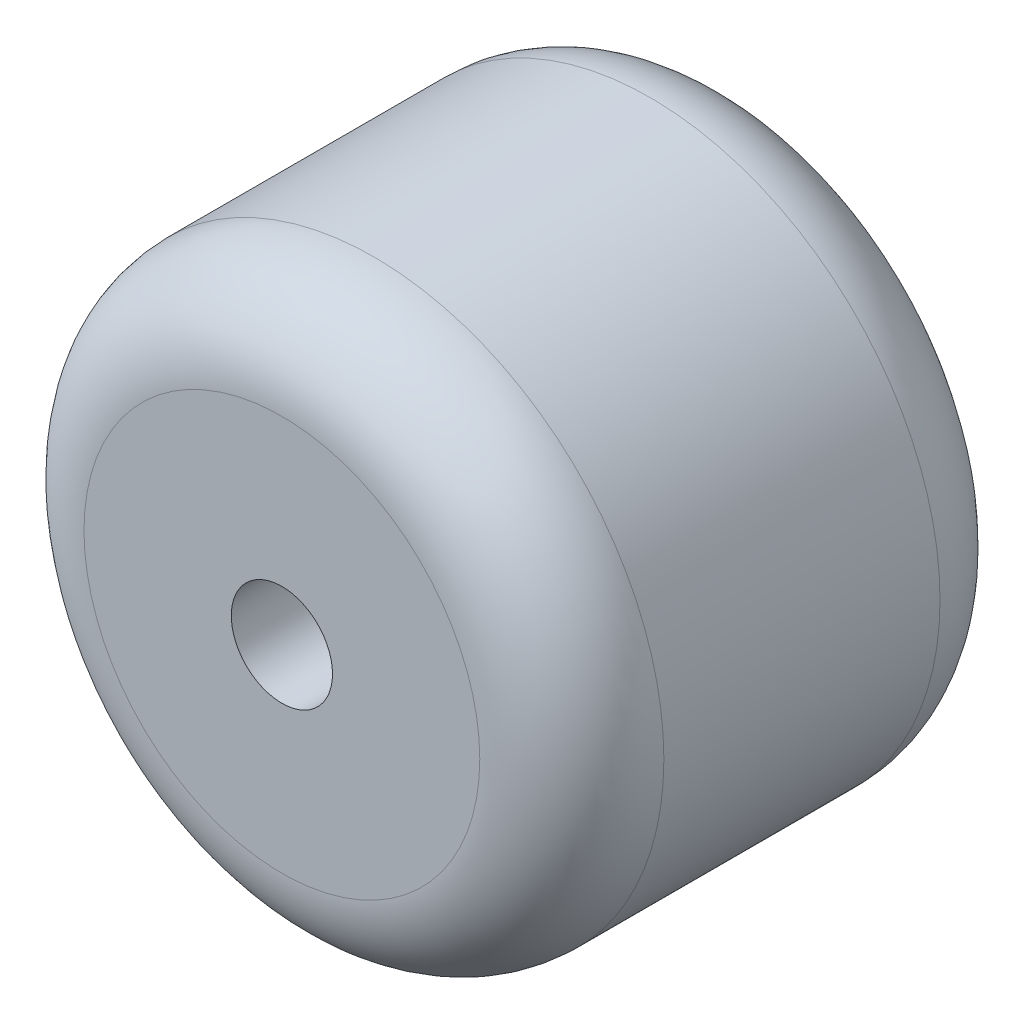
SolidWorks part; units mm, degrees
ref_plane "前视基准面" through (0, 0, 0) normal (0, 0, 1) x (1, 0, 0)
ref_plane "上视基准面" through (0, 0, 0) normal (0, 1, 0) x (1, 0, 0)
ref_plane "右视基准面" through (0, 0, 0) normal (1, 0, 0) x (0, 0, -1)
other "Configuration Table"
sketch "草图1" plane through (0, 0, 0) normal (0, 0, 1) x (1, 0, 0)
  circle A0 centre (0, 0) radius 2.75
  circle A1 centre (0, 0) radius 15.75
  dimension "D1" = 31.5
  dimension "D2" = 5.5
extrude "凸台-拉伸1" add sketch "草图1" along normal blind 25
fillet "圆角1" radius 5 2 edges at (15.75, 0, 25) (15.75, 0, 0)
